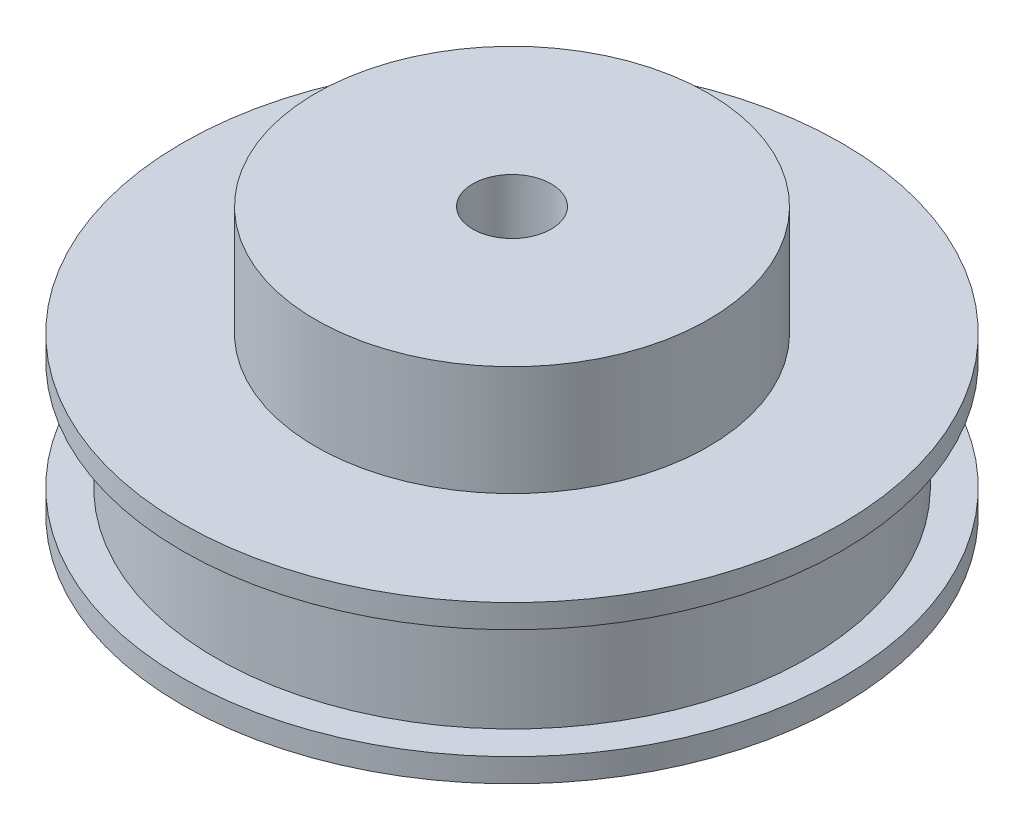
SolidWorks part; units mm, degrees
material "1060 Alloy"
ref_plane "Front Plane" through (0, 0, 0) normal (0, 0, 1) x (1, 0, 0)
ref_plane "Top Plane" through (0, 0, 0) normal (0, 1, 0) x (1, 0, 0)
ref_plane "Right Plane" through (0, 0, 0) normal (1, 0, 0) x (0, 0, -1)
sketch "Sketch1" plane through (0, 0, 0) normal (0, 0, 1) x (1, 0, 0)
  line L0 (2.5, 0) -> (2.5, 17)
  line L1 (2.5, 17) -> (12.5, 17)
  line L2 (12.5, 17) -> (12.5, 10)
  line L3 (12.5, 10) -> (21, 10)
  line L5 (21, 0) -> (2.5, 0)
  line L6 (0, 0) -> (0, 14.4128) construction
  line L7 (21, 10) -> (21, 8.5)
  line L8 (21, 8.5) -> (18.84, 8.5)
  line L9 (18.84, 8.5) -> (18.84, 1.5)
  line L10 (18.84, 1.5) -> (21, 1.5)
  line L11 (21, 1.5) -> (21, 0)
  dimension "D1" = 5
  dimension "D2" = 25
  dimension "D3" = 1.5
  dimension "D4" = 7
  dimension "D5" = 7
  dimension "D6" = 42
  dimension "D7" = 37.68
revolve "Revolve1" add sketch "Sketch1" angle 360 about L6
